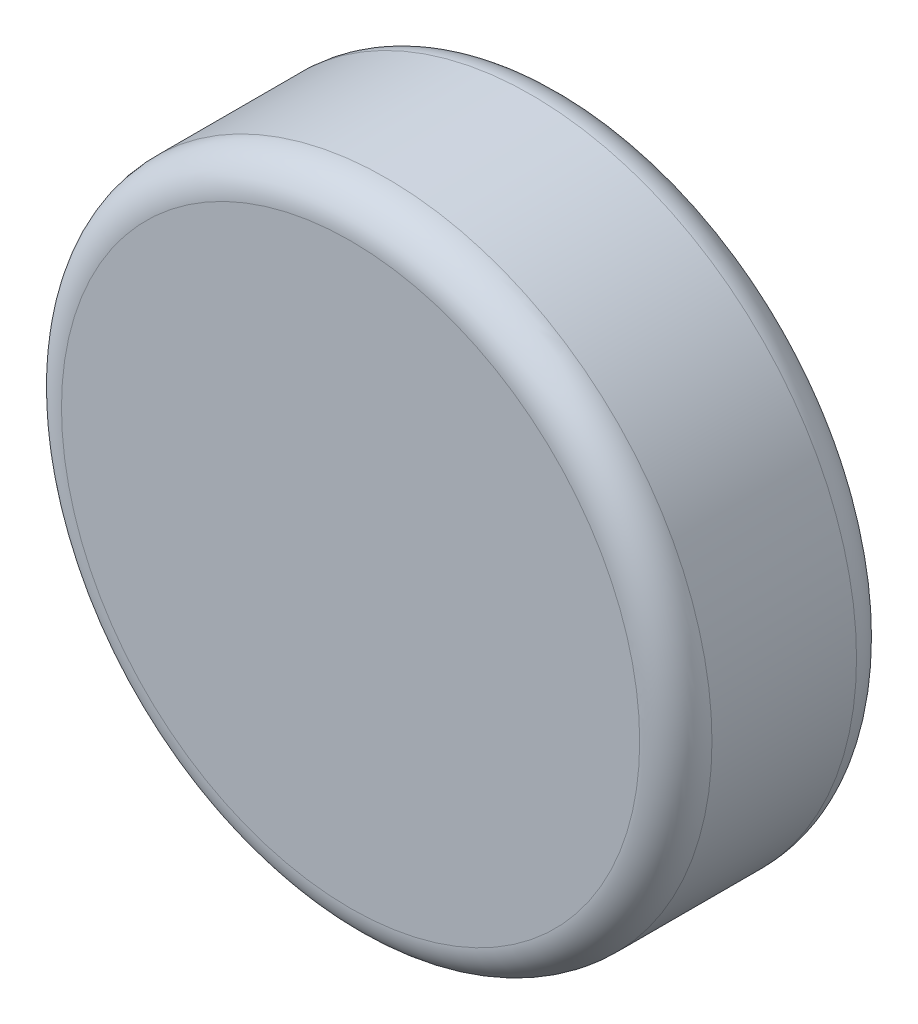
SolidWorks part; units mm, degrees
ref_plane "Front Plane" through (0, 0, 0) normal (0, 0, 1) x (1, 0, 0)
ref_plane "Top Plane" through (0, 0, 0) normal (0, 1, 0) x (1, 0, 0)
ref_plane "Right Plane" through (0, 0, 0) normal (1, 0, 0) x (0, 0, -1)
sketch "Sketch1" plane through (0, 0, 0) normal (0, 0, 1) x (1, 0, 0)
  circle A0 centre (89.4937, -41.883) radius 45
extrude "Boss-Extrude1" add sketch "Sketch1" along normal blind 30
fillet "Fillet1" radius 5 2 edges at (134.4937, -41.883, 0) (134.4937, -41.883, 30)
